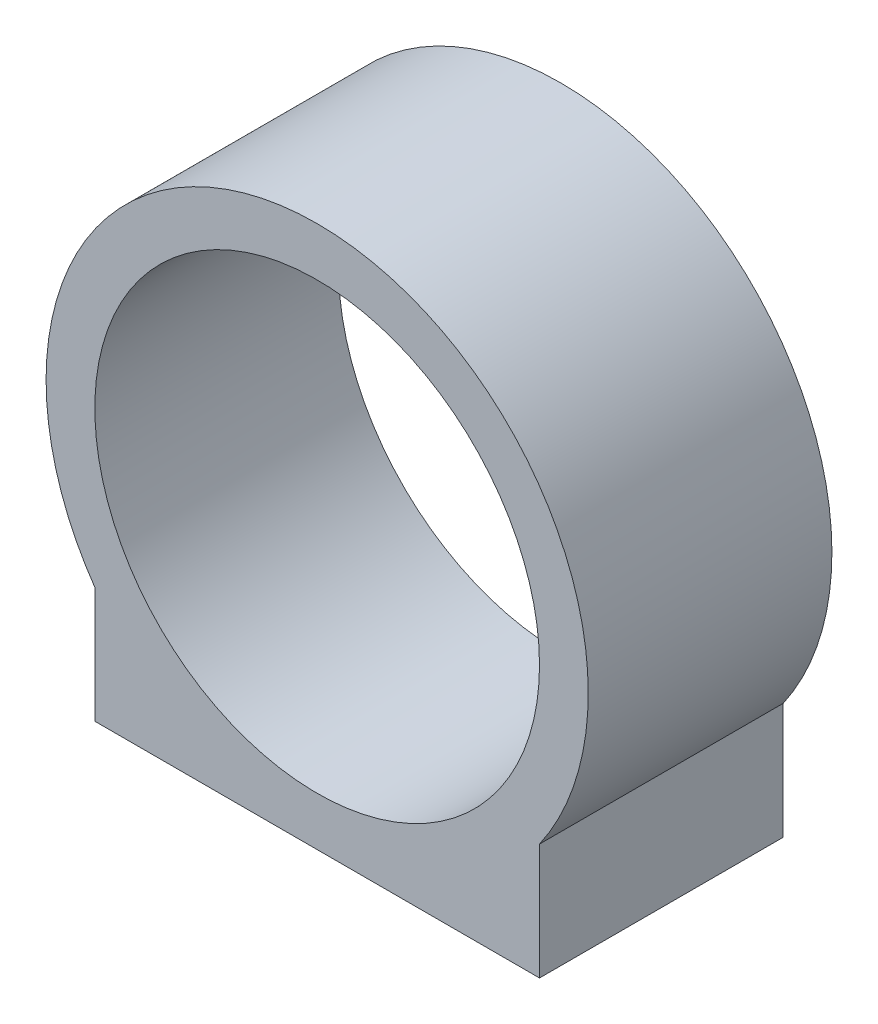
SolidWorks part; units mm, degrees
ref_plane "Front" through (0, 0, 0) normal (0, 0, 1) x (1, 0, 0)
ref_plane "Top" through (0, 0, 0) normal (0, 1, 0) x (1, 0, 0)
ref_plane "Right" through (0, 0, 0) normal (1, 0, 0) x (0, 0, -1)
sketch "Sketch1" plane through (0, 0, 0) normal (0, 0, 1) x (1, 0, 0)
  circle A0 centre (0, 0) radius 9.125
  circle A1 centre (0, 0) radius 11.125
  dimension "D1" = 18.25
  dimension "D2" = 2
extrude "Boss-Extrude1" add sketch "Sketch1" along normal blind 10
sketch "Sketch2" plane through (0, 0, 10) normal (0, 0, 1) x (1, 0, 0)
  line L0 (9.125, -11.125) -> (9.125, -9.125)
  line L1 (9.125, -11.125) -> (-9.125, -11.125)
  line L2 (0, -11.125) -> (0, -9.125)
  line L3 (9.125, -9.125) -> (-9.125, -9.125)
  line L4 (-9.125, -11.125) -> (-9.125, -9.125)
  line L5 (-9.125, -9.125) -> (-9.125, -6.364)
  line L6 (-9.125, -6.364) -> (-4.6463, -9.125)
  line L7 (-4.6463, -9.125) -> (4.4394, -9.125)
  line L8 (4.4394, -9.125) -> (9.125, -6.364)
  line L9 (9.125, -6.364) -> (9.125, -9.125)
  circle A1 centre (0, 0) radius 11.125 construction
  circle M3 centre (0, 0) radius 11.125
extrude "Boss-Extrude2" add sketch "Sketch2" against normal up to surface (10 mm away) contours L5 L3 M3 | L4 L1 L3 M3 | L0 L3 L1 M3 | L9 L3 M3 up to face at (11.125, 0, 0)
